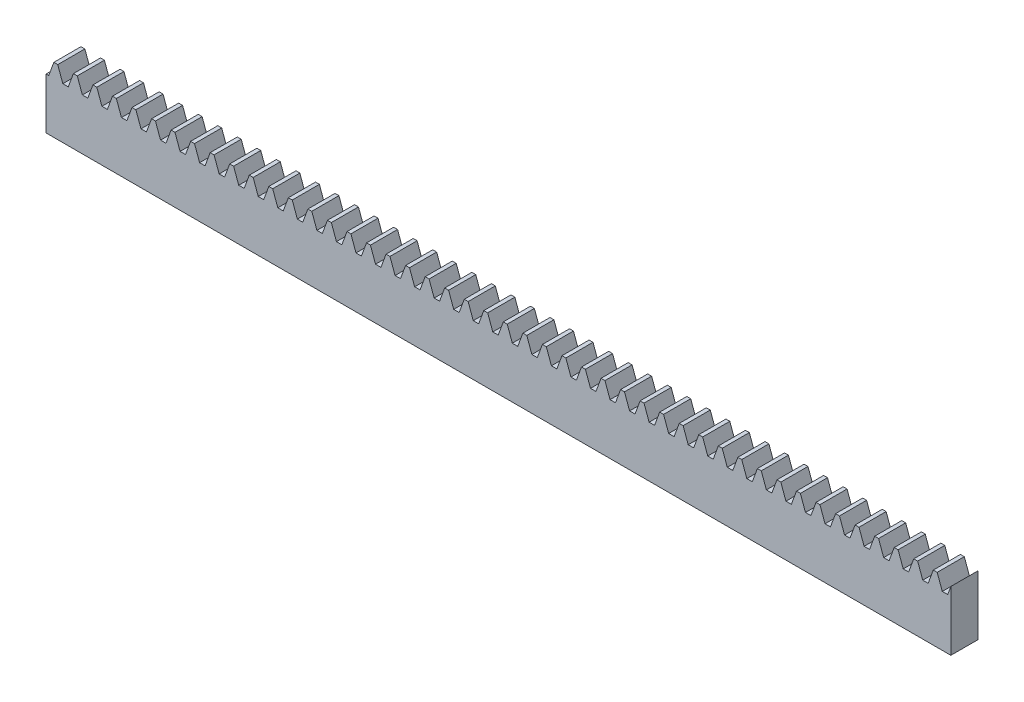
SolidWorks part; units mm, degrees
extrude "Blank" add sketch "BlankSke" against normal blind 6
sketch "BlankSke" plane through (0, 0, 0) normal (0, 0, 1) x (1, 0, 0)
  line L1 (0, 0) -> (200, 0)
  line L2 (0, 0) -> (0, 14.375)
  line L3 (0, 14.375) -> (200, 14.375)
  line L4 (200, 0) -> (200, 14.375)
  dimension "Length" = 200
  dimension "Blank_height" = 14.375
material "ABS"
ref_plane "Plane1" through (0, 0, 0) normal (0, 0, 1) x (1, 0, 0)
ref_plane "Plane2" through (0, 0, 0) normal (0, 1, 0) x (1, 0, 0)
ref_plane "Plane3" through (0, 0, 0) normal (1, 0, 0) x (0, 0, -1)
sketch "HoldingSke" plane through (0, 0, 0) normal (0, 1, 0) x (1, 0, 0)
  line L0 (0, 0) -> (0.1012, 0.7202)
  line L1 (-15, 0) -> (100, 0) construction
  line L2 (0, 0) -> (-2.1039, 2.3779)
  line L3 (0, 0) -> (-11.863, 4.5341)
  line L4 (0, 0) -> (5.7786, 6.4178)
  line L5 (0, 0) -> (-23.7986, -8.8762)
  line L6 (0, 0) -> (-10.5278, -7.1032)
  line L9 (-71.009, 38.7566) -> (116.9296, 107.1606)
  line L10 (-76.2, 3.7529) -> (-63.2, 3.7529)
  line L11 (0, 0) -> (-6, 0)
  line L12 (-76.2, 101.6) -> (-76.151, 101.6)
  line L13 (24.9733, 27.94) -> (52.9518, 28.4284)
  line L14 (24.9733, 27.94) -> (24.9743, 27.94)
  line L15 (24.9733, 27.94) -> (100.4006, 29.5858)
  circle A0 centre (0, 0) radius 19.05
  circle A1 centre (0, 0) radius 6.5
  circle A2 centre (0, 0) radius 12.7
  dimension "MPH" = 13
  dimension "Diameter" = 38.1
  dimension "Num_teeth" = 48
  dimension "Pitch" = 0.7273
  dimension "Show_teeth" = 998
  dimension "Thickness" = 12.7
  dimension "Ap" = 20
  dimension "Pitch_height" = 13
  dimension "Width" = 6
  dimension "Backlash" = 0.049
  dimension "Addendum_fac" = 1
  dimension "Dedendum_fac" = 1.25
  dimension "Clearance_fac" = 0.25
  dimension "Dedendum_add" = 0.001
  dimension "Length" = 200
  dimension "Module" = 1.375
sketch "TooCutSkeIll" plane through (0, 0, 0) normal (0, 0, 1) x (1, 0, 0)
  line L0 (-1.7142, 14.3388) -> (-0.6839, 11.5081)
  line L1 (-0.36, 11.2812) -> (0.36, 11.2812)
  line L2 (0.6839, 11.5081) -> (1.7142, 14.3388)
  line L3 (200, 14.375) -> (0, 14.375) construction
  line L4 (0, 0) -> (0, 64.897) construction
  line L5 (-13.208, 13) -> (12.954, 13) construction
  line L6 (0, 0) -> (200, 0) construction
  line L7 (1.2269, 13) -> (1.2269, 48.7463) construction
  line L8 (-1.2269, 13) -> (-1.2269, 48.7463) construction
  line L9 (1.7659, 14.375) -> (1.7659, 14.4004)
  line L10 (-1.7659, 14.375) -> (-1.7659, 14.4004)
  line L11 (-1.7659, 14.4004) -> (1.7659, 14.4004)
  arc A0 (0.36, 11.2812) -> (0.6839, 11.5081) centre (0.36, 11.626) ccw
  arc A1 (-0.6839, 11.5081) -> (-0.36, 11.2812) centre (-0.36, 11.626) ccw
  arc A2 (1.7659, 14.375) -> (1.7142, 14.3388) centre (1.7659, 14.32) ccw
  arc A3 (-1.7142, 14.3388) -> (-1.7659, 14.375) centre (-1.7659, 14.32) ccw
  dimension "Pitch_height" = 13
  dimension "Addendum_plus" = 1.4004
  dimension "Pressure_angle" = 20
  dimension "Gap_width" = 2.4538
  dimension "Dedendum" = 1.7188
extrude "ToothCutIll" [suppressed] cut sketch "TooCutSkeIll" against normal through all
sketch "TooCutSkeSim" plane through (0, 0, 0) normal (0, 0, 1) x (1, 0, 0)
  line L0 (0.6013, 11.2812) -> (-0.6013, 11.2812)
  line L1 (1.7366, 14.4004) -> (0.6013, 11.2812)
  line L2 (0, 17.4625) -> (0, 53.467) construction
  line L3 (1.7366, 14.4004) -> (-1.7366, 14.4004)
  line L6 (-1.7366, 14.4004) -> (-0.6013, 11.2812)
  line L9 (-1.2269, 13) -> (1.2269, 13) construction
  line L10 (0, 0) -> (200, 0) construction
  line L11 (1.2269, 13) -> (1.2269, 53.467) construction
  line L12 (-1.2269, 13) -> (-1.2269, 53.467) construction
  dimension "Pitch_height" = 13
  dimension "Addendum_plus" = 1.4004
  dimension "Pressure_angle" = 20
  dimension "Gap_width" = 2.4538
  dimension "Dedendum" = 1.7188
extrude "ToothCutSim" cut sketch "TooCutSkeSim" against normal through all
pattern_linear "TeethCuts" count 47 spacing 4.3197 along (1, 0, 0) of "ToothCutIll", "ToothCutSim"
equation "' \"Module@HoldingSke\" = 6.35"
equation "' \"Num_teeth@HoldingSke\" = 12"
equation "' \"Ap@HoldingSke\" =  20"
equation "' \"Ap@HoldingSke\" = 20"
equation "' \"Width@HoldingSke\" = 0.25 * 25.4"
equation "' \"Show_teeth@HoldingSke\" = 500"
equation "' \"Backlash@HoldingSke\" = 0.009 * 25.4"
equation "' \"Addendum_fac@HoldingSke\" = 1.0"
equation "' \"Dedendum_fac@HoldingSke\" = 1.25"
equation "' \"Dedendum_add@HoldingSke\" = 0.00005 * 25.4"
equation "' \"Clearance_fac@HoldingSke\" = 0.25"
equation "' \"Pitch_height@HoldingSke\" = 1 * 25.4"
equation "' \"Length@HoldingSke\" = 4.71 * 25.4"
equation "\"Pitch@HoldingSke\" = 1 / \"Module@HoldingSke\""
equation "\"MPH@HoldingSke\" = \"Dedendum_fac@HoldingSke\" / \"Pitch@HoldingSke\" + 2 * \"Dedendum_add@HoldingSke\" + 0.002 * 25.4"
equation "\"MPH@HoldingSke\" = ((sgn( \"MPH@HoldingSke\" - \"Pitch_height@HoldingSke\")+1)*( \"MPH@HoldingSke\" - \"Pitch_height@HoldingSke\"))/2 + \"Pitch_height@HoldingSke\""
equation "\"Blank_height@BlankSke\" = \"Pitch_height@HoldingSke\" + \"Addendum_fac@HoldingSke\"  / \"Pitch@HoldingSke\" "
equation "\"Length@BlankSke\" =  \"Length@HoldingSke\""
equation "\"Face_width@Blank\" = \"Width@HoldingSke\""
equation "\"Pressure_angle@TooCutSkeIll\" = \"Ap@HoldingSke\""
equation "\"Addendum_plus@TooCutSkeIll\" =  \"Addendum_fac@HoldingSke\"  / \"Pitch@HoldingSke\" + 0.001 *25.4"
equation "\"Dedendum@TooCutSkeIll\" = \"Dedendum_fac@HoldingSke\"  / \"Pitch@HoldingSke\""
equation "\"Pitch_height@TooCutSkeIll\" =  \"MPH@HoldingSke\""
equation "\"Gap_width@TooCutSkeIll\" = 3.14159265 / 2 / \"Pitch@HoldingSke\" + 6 * \"Backlash@HoldingSke\""
equation "\"Pressure_angle@TooCutSkeSim\" = \"Ap@HoldingSke\""
equation "\"Addendum_plus@TooCutSkeSim\" =  \"Addendum_fac@HoldingSke\"  / \"Pitch@HoldingSke\" + 0.001 * 25.4"
equation "\"Dedendum@TooCutSkeSim\" = \"Dedendum_fac@HoldingSke\"  / \"Pitch@HoldingSke\""
equation "\"Pitch_height@TooCutSkeSim\" =  \"MPH@HoldingSke\""
equation "\"Gap_width@TooCutSkeSim\" = 3.14159265 / 2 / \"Pitch@HoldingSke\" + 6 * \"Backlash@HoldingSke\""
equation "\"Root_fillet@TooCutSkeIll\" = \"Clearance_fac@HoldingSke\" / \"Pitch@HoldingSke\" + \"Dedendum_add@HoldingSke\""
equation "\"Break_rad@TooCutSkeIll\" = 0.02 / \"Pitch@HoldingSke\" * 2"
equation "\"Linear_pitch@TeethCuts\" = 3.14159265 / \"Pitch@HoldingSke\""
equation "\"Num_teeth@HoldingSke\" = int( ( \"Length@HoldingSke\" + 0 ) / (3.14159265 / \"Pitch@HoldingSke\")) + 0.9999  + 1"
equation " \"Num_teeth@TeethCuts\" = int( \"Show_teeth@HoldingSke\" ) + 1"
equation " \"Num_teeth@TeethCuts\" = ((sgn( \"Num_teeth@TeethCuts\" - \"Num_teeth@HoldingSke\" )-1)*( \"Num_teeth@TeethCuts\" - \"Num_teeth@HoldingSke\" ))/-2+ \"Num_teeth@HoldingSke\""
equation " \"Num_teeth@TeethCuts\" = ((sgn( \"Num_teeth@TeethCuts\" - 2.0)+1)*( \"Num_teeth@TeethCuts\" - 2.0))/2 +2.0"
